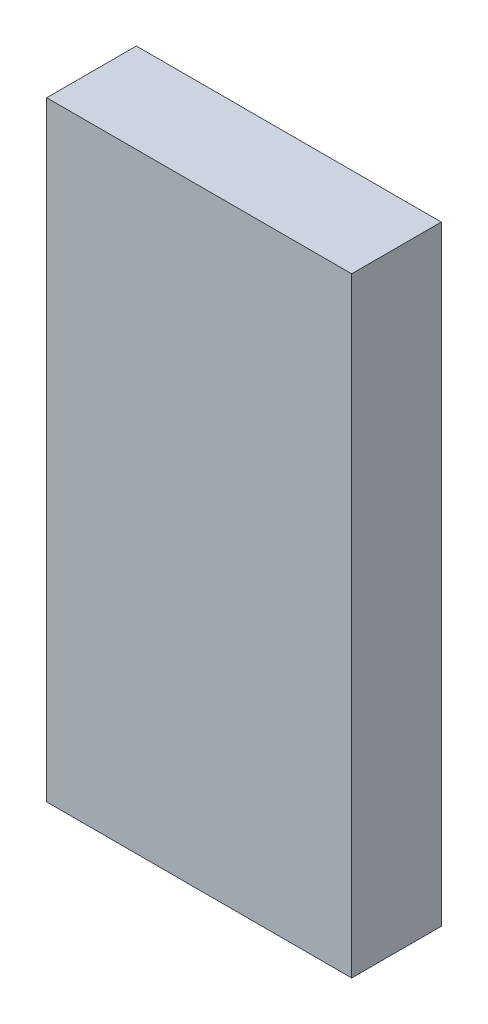
SolidWorks part; units mm, degrees
material "Pure Lead"
ref_plane "Front Plane" through (0, 0, 0) normal (0, 0, 1) x (1, 0, 0)
ref_plane "Top Plane" through (0, 0, 0) normal (0, 1, 0) x (1, 0, 0)
ref_plane "Right Plane" through (0, 0, 0) normal (1, 0, 0) x (0, 0, -1)
sketch "Sketch1" plane through (0, 0, 0) normal (0, 0, 1) x (1, 0, 0)
  line L1 (122.5, -245) -> (-122.5, -245)
  line L2 (122.5, -245) -> (122.5, 245)
  line L3 (122.5, 245) -> (-122.5, 245)
  line L4 (-122.5, -245) -> (-122.5, 245)
  line L5 (122.5, -245) -> (-122.5, 245) construction
  line L6 (122.5, 245) -> (-122.5, -245) construction
  point P0 (0, 0)
  dimension "D1" = 245
  dimension "D2" = 490
extrude "Boss-Extrude1" add sketch "Sketch1" along normal blind 72 contours L3 L4 L1 L2
